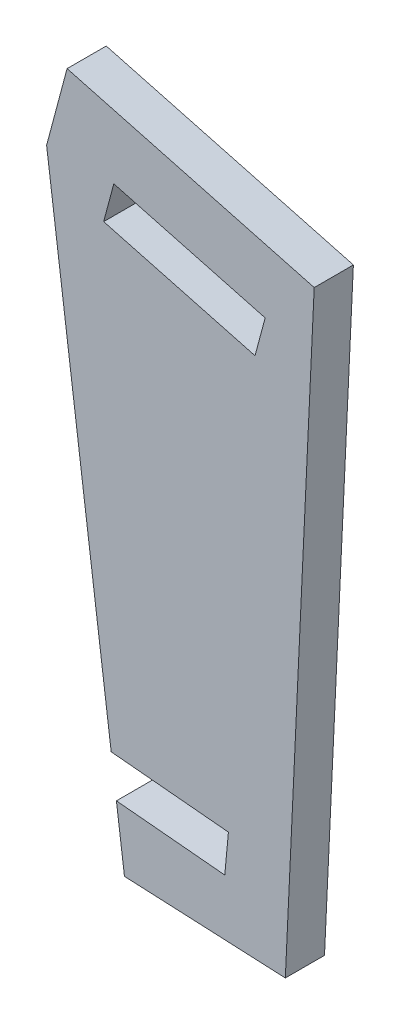
SolidWorks part; units mm, degrees
ref_plane "Front" through (0, 0, 0) normal (0, 0, 1) x (1, 0, 0)
ref_plane "Top" through (0, 0, 0) normal (0, 1, 0) x (1, 0, 0)
ref_plane "Right" through (0, 0, 0) normal (1, 0, 0) x (0, 0, -1)
sketch "Sketch1" plane through (0, 0, 0) normal (0, 0, 1) x (1, 0, 0)
  line L0 (156.0497, -56.982) -> (160.996, -94.74)
  line L1 (176.5449, -56.1715) -> (174.3325, -103.0729)
  line L2 (160.996, -94.74) -> (169.9731, -95.5765)
  line L3 (174.3325, -103.0729) -> (162.0114, -102.4917)
  line L4 (161.3955, -97.7902) -> (169.6947, -98.5635)
  line L5 (161.3955, -97.7902) -> (162.0114, -102.4917)
  line L6 (169.9731, -95.5765) -> (169.6947, -98.5635)
  line L7 (160.4198, -59.8622) -> (172.013, -62.96)
  line L8 (172.013, -62.96) -> (172.7875, -60.0617)
  line L9 (172.7875, -60.0617) -> (161.1942, -56.9639)
  line L10 (161.1942, -56.9639) -> (160.4198, -59.8622)
  line L11 (157.6176, -51.114) -> (176.5449, -56.1715)
  line L12 (157.6176, -51.114) -> (156.0497, -56.982)
  dimension "D1" = 3
  dimension "D2" = 90
  dimension "D3" = 90
  dimension "D4" = 3
  dimension "D5" = 90
  dimension "D6" = 90
  dimension "D7" = 12
extrude "Base-Extrude" add sketch "Sketch1" along normal blind 3
